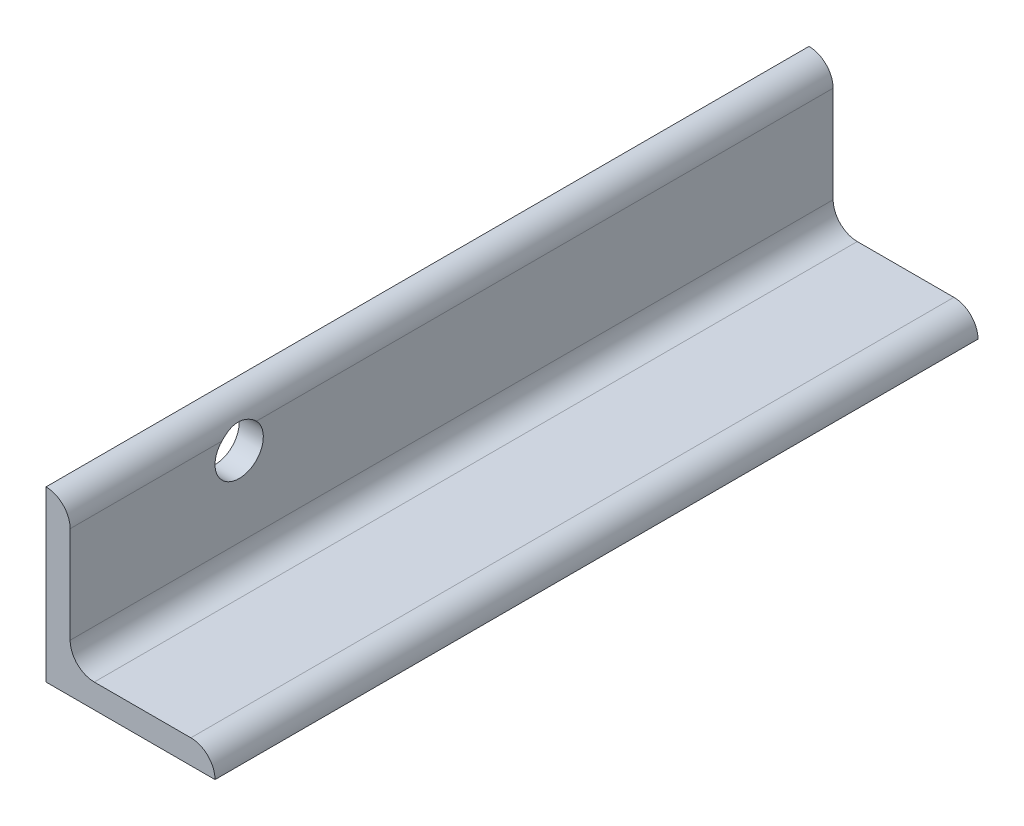
SolidWorks part; units mm, degrees
ref_plane "Płaszczyzna przednia" through (0, 0, 0) normal (0, 0, 1) x (1, 0, 0)
ref_plane "Płaszczyzna górna" through (0, 0, 0) normal (0, 1, 0) x (1, 0, 0)
ref_plane "Płaszczyzna prawa" through (0, 0, 0) normal (1, 0, 0) x (0, 0, -1)
sketch "Szkic1" plane through (0, 0, 0) normal (1, 0, 0) x (0, 0, -1)
  line L0 (-79, 0) -> (79, 0)
  point P3 (0, 0)
  dimension "D1" = 158
other "Kątownik stalowy 35 X 35 X 5(1)"
ref_plane "Płaszczyzna1" through (0, 0, 79) normal (0, 0, -1) x (0, 1, 0)
sketch "Sketch1" plane through (0, 0, 79) normal (0, 0, -1) x (0, 1, 0)
  line L0 (0, 0) -> (0, 35)
  line L1 (0, 17.5) -> (5, 17.5) construction
  line L2 (5, 30) -> (5, 10)
  line L3 (10, 5) -> (30, 5)
  line L4 (17.5, 5) -> (17.5, 0) construction
  line L5 (35, 0) -> (0, 0)
  arc A0 (35, 0) -> (30, 5) centre (30, 0) ccw
  arc A1 (0, 35) -> (5, 30) centre (0, 30) cw
  arc A2 (10, 5) -> (5, 10) centre (10, 10) cw
  point P10 (17.5, 0)
  point P14 (0, 17.5)
  point P15 (5, 17.5)
  point P16 (17.5, 5)
  point P17 (5, 35)
  point P18 (35, 5)
  point P21 (0, 0)
  dimension "D2" = 5
  dimension "D3" = 35
  dimension "Radius_1" = 5
  dimension "D1" = 5
sketch "Szkic3" plane through (0, 0, 0) normal (-1, 0, 0) x (0, 0, 1)
  line L0 (-79, 35) -> (79, 35) construction
  line L1 (79, 0) -> (79, 35) construction
  circle A0 centre (44, 26.5) radius 5
  dimension "D1" = 10
  dimension "D2" = 8.5
  dimension "D3" = 35
extrude "Wytnij-wyciągnięcie1" cut sketch "Szkic3" against normal blind 10
